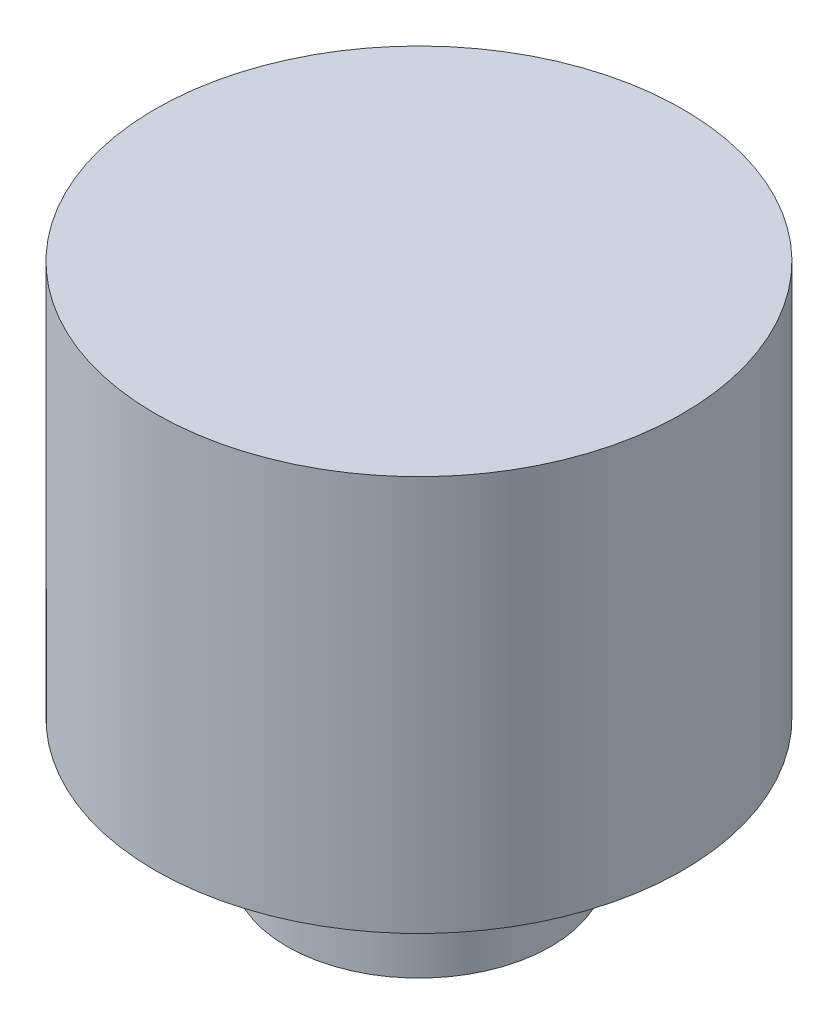
SolidWorks part; units mm, degrees
ref_plane "Front Plane" through (0, 0, 0) normal (0, 0, 1) x (1, 0, 0)
ref_plane "Top Plane" through (0, 0, 0) normal (0, 1, 0) x (1, 0, 0)
ref_plane "Right Plane" through (0, 0, 0) normal (1, 0, 0) x (0, 0, -1)
sketch "Sketch1" plane through (0, 0, 0) normal (0, 1, 0) x (1, 0, 0)
  circle A0 centre (0, 0) radius 1
  dimension "D1" = 2
extrude "Boss-Extrude1" add sketch "Sketch1" along normal blind 1
sketch "Sketch2" plane through (0, 1, 0) normal (0, 1, 0) x (1, 0, 0)
  circle A0 centre (0, 0) radius 2
  dimension "D1" = 4
extrude "Boss-Extrude2" add sketch "Sketch2" along normal blind 3
